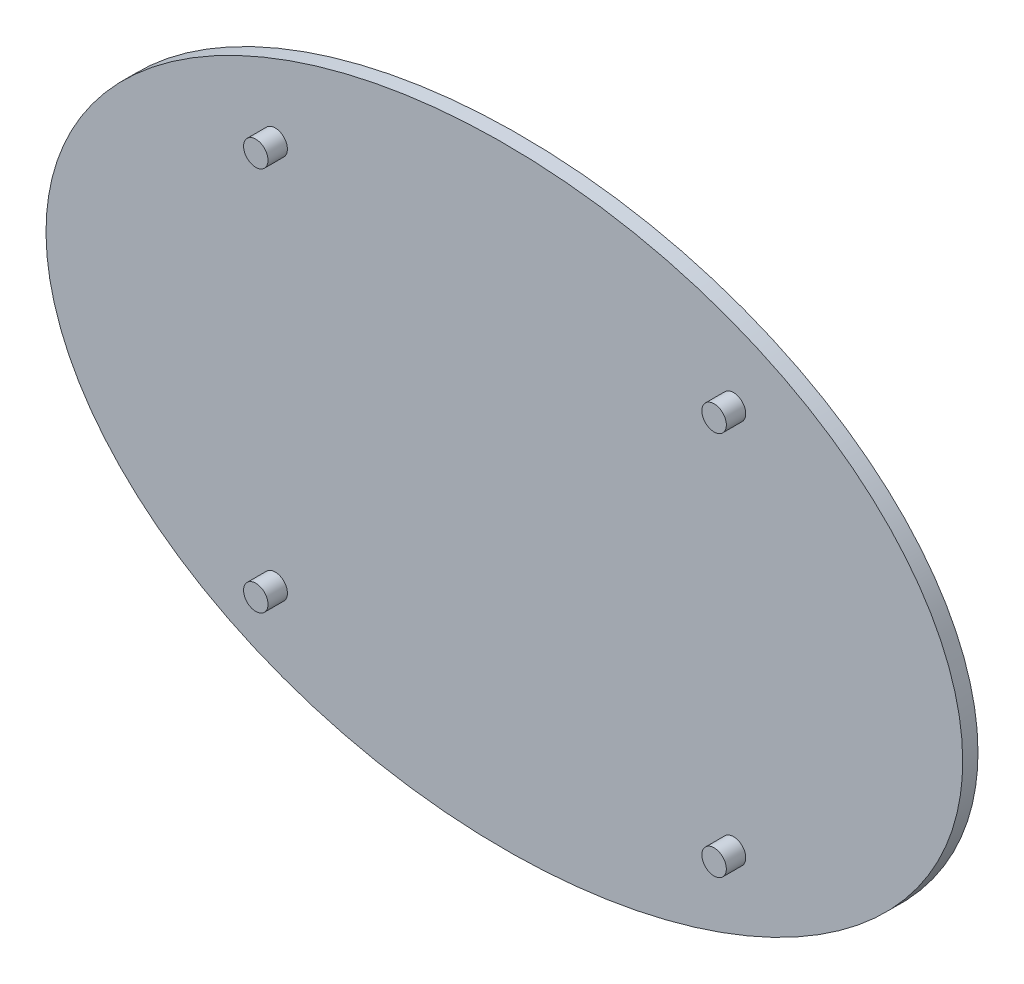
SolidWorks part; units mm, degrees
material "Plain Carbon Steel"
ref_plane "Front" through (0, 0, 0) normal (0, 0, 1) x (1, 0, 0)
ref_plane "Top" through (0, 0, 0) normal (0, 1, 0) x (1, 0, 0)
ref_plane "Right" through (0, 0, 0) normal (1, 0, 0) x (0, 0, -1)
ref_plane "Plane1" through (0, 0, 5) normal (0, 0, 1) x (1, 0, 0)
sketch "Sketch1" plane through (0, 0, 5) normal (0, 0, 1) x (1, 0, 0)
  ellipse E0 centre (0, 0) end of major axis (150, 0) minor radius 100
  point P0 (0, 0)
  point P1 (150, 0)
  point P2 (0, -100)
extrude "Boss-Extrude1" add sketch "Sketch1" against normal blind 5
sketch "Sketch2" plane through (0, 0, 5) normal (0, 0, 1) x (1, 0, 0)
  line L0 (50, 0) -> (-50, 0) construction
  line L1 (0, -50) -> (0, 50) construction
  circle A0 centre (-74.9931, -62.9266) radius 4
  circle A1 centre (-74.9931, 62.9266) radius 4
  circle A2 centre (74.9931, 62.9266) radius 4
  circle A3 centre (74.9931, -62.9266) radius 4
extrude "Boss-Extrude2" add sketch "Sketch2" along normal blind 6.35
